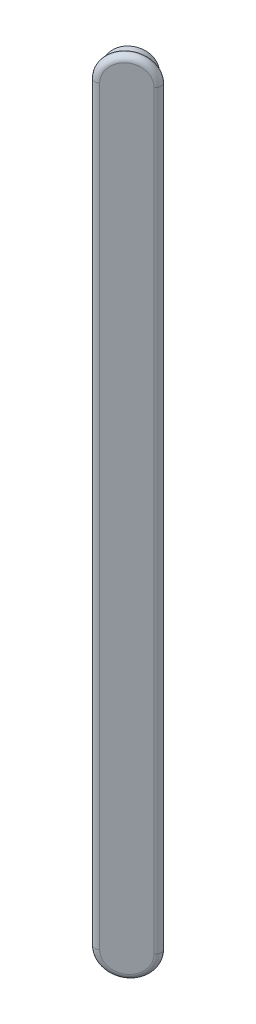
SolidWorks part; units mm, degrees
ref_plane "Front Plane" through (0, 0, 0) normal (0, 0, 1) x (1, 0, 0)
ref_plane "Top Plane" through (0, 0, 0) normal (0, 1, 0) x (1, 0, 0)
ref_plane "Right Plane" through (0, 0, 0) normal (1, 0, 0) x (0, 0, -1)
ref_plane "Plane1" through (-3679.7835, 0, -4864.0005) normal (-0.6033, 0, -0.7975) x (0, -1, 0)
sketch "Sketch1" plane through (-3679.7835, 0, -4864.0005) normal (-0.6033, 0, -0.7975) x (0, -1, 0)
  line L0 (-531.631, 8466.3058) -> (-709.631, 8466.3058)
  line L1 (-709.631, 8454.3058) -> (-531.631, 8454.3058)
  arc A0 (-531.631, 8454.3058) -> (-531.631, 8466.3058) centre (-531.631, 8460.3058) ccw
  arc A1 (-709.631, 8466.3058) -> (-715.631, 8460.3058) centre (-709.631, 8460.3058) ccw
  arc A2 (-715.631, 8460.3058) -> (-709.631, 8454.3058) centre (-709.631, 8460.3058) ccw
extrude "Boss-Extrude1" add sketch "Sketch1" against normal blind 1.5
sketch "Sketch2" plane through (-3679.7835, 0, -4864.0005) normal (-0.6033, 0, -0.7975) x (-0.7975, 0, 0.6033)
  line L0 (8455.4058, 531.631) -> (8455.4058, 709.631)
  line L1 (8465.2058, 709.631) -> (8465.2058, 531.631)
  arc A0 (8465.2058, 531.631) -> (8455.4058, 531.631) centre (8460.3058, 531.631) cw
  arc A1 (8455.4058, 709.631) -> (8460.3058, 714.531) centre (8460.3058, 709.631) cw
  arc A2 (8460.3058, 714.531) -> (8465.2058, 709.631) centre (8460.3058, 709.631) cw
extrude "Boss-Extrude2" add sketch "Sketch2" along normal blind 3
sketch "Sketch3" plane through (-3681.5935, 0, -4866.393) normal (-0.6033, 0, -0.7975) x (-0.7975, 0, 0.6033)
  line L0 (8463.7058, 531.631) -> (8463.7058, 709.631)
  line L1 (8456.9058, 709.631) -> (8456.9058, 531.631)
  arc A0 (8456.9058, 531.631) -> (8463.7058, 531.631) centre (8460.3058, 531.631) ccw
  arc A1 (8463.7058, 709.631) -> (8460.3058, 713.031) centre (8460.3058, 709.631) ccw
  arc A2 (8460.3058, 713.031) -> (8456.9058, 709.631) centre (8460.3058, 709.631) ccw
extrude "Cut-Extrude1" cut sketch "Sketch3" against normal blind 3
fillet "Fillet1" radius 1.4002 4 edges at (-10425.9024, 715.631, 241.551) (-10421.1174, 620.631, 237.931) (-10430.6873, 620.631, 245.171) (-10425.9024, 525.631, 241.551)
sketch "Sketch4" plane through (-3681.5935, 0, -4866.393) normal (-0.6033, 0, -0.7975) x (-0.7975, 0, 0.6033)
  line L0 (8463.7058, 531.631) -> (8463.7058, 709.631) construction
  line L8 (8456.9058, 681.731) -> (8463.7058, 681.731)
  line L9 (8456.9058, 681.731) -> (8456.9058, 682.731)
  line L10 (8456.9058, 682.731) -> (8463.7058, 682.731)
  line L11 (8463.7058, 681.731) -> (8463.7058, 682.731)
  line L12 (8456.9058, 681.731) -> (8463.7058, 682.731) construction
  line L13 (8456.9058, 682.731) -> (8463.7058, 681.731) construction
  line L14 (8456.9058, 651.931) -> (8463.7058, 651.931)
  line L15 (8463.7058, 650.931) -> (8463.7058, 651.931)
  line L16 (8456.9058, 650.931) -> (8463.7058, 650.931)
  line L17 (8456.9058, 650.931) -> (8456.9058, 651.931)
  line L18 (8456.9058, 621.131) -> (8463.7058, 621.131)
  line L19 (8463.7058, 620.131) -> (8463.7058, 621.131)
  line L20 (8456.9058, 620.131) -> (8463.7058, 620.131)
  line L21 (8456.9058, 620.131) -> (8456.9058, 621.131)
  line L22 (8456.9058, 590.331) -> (8463.7058, 590.331)
  line L23 (8463.7058, 589.331) -> (8463.7058, 590.331)
  line L24 (8456.9058, 589.331) -> (8463.7058, 589.331)
  line L25 (8456.9058, 589.331) -> (8456.9058, 590.331)
  line L26 (8456.9058, 559.531) -> (8463.7058, 559.531)
  line L27 (8463.7058, 558.531) -> (8463.7058, 559.531)
  line L28 (8456.9058, 558.531) -> (8463.7058, 558.531)
  line L29 (8456.9058, 558.531) -> (8456.9058, 559.531)
  point P0 (8460.3058, 682.231)
  dimension "D1" = 1
  dimension "D3" = 5
extrude "Boss-Extrude3" add sketch "Sketch4" against normal up to next contours L28 L27 L26 L29 | L22 L23 L24 L25 | L20 L19 L18 L21 | L14 L15 L16 L17 | L10 L11 L8 L9
